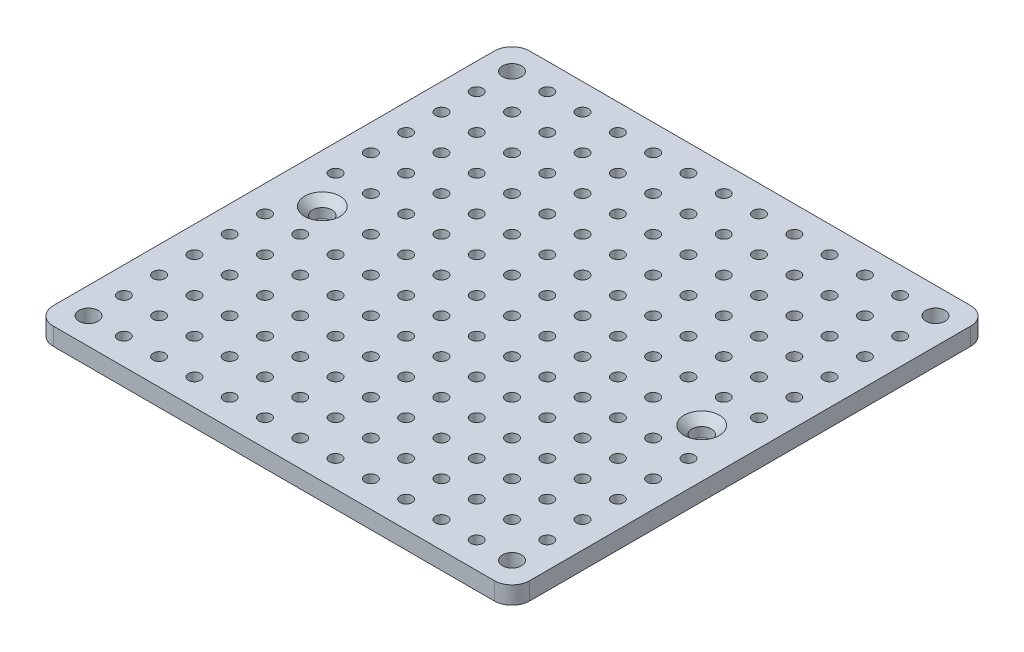
SolidWorks part; units mm, degrees
material "1060 Alloy"
ref_plane "Front Plane" through (0, 0, 0) normal (0, 0, 1) x (1, 0, 0)
ref_plane "Top Plane" through (0, 0, 0) normal (0, 1, 0) x (1, 0, 0)
ref_plane "Right Plane" through (0, 0, 0) normal (1, 0, 0) x (0, 0, -1)
sketch "Sketch1" plane through (0, 0, 0) normal (0, 1, 0) x (1, 0, 0)
  line L1 (-135, 135) -> (135, 135)
  line L2 (-135, 135) -> (-135, -135)
  line L3 (-135, -135) -> (135, -135)
  line L4 (135, 135) -> (135, -135)
  line L5 (-135, 135) -> (135, -135) construction
  line L6 (-135, -135) -> (135, 135) construction
  point P0 (0, 0)
  dimension "D1" = 270
  dimension "D2" = 270
extrude "Boss-Extrude1" add sketch "Sketch1" along normal blind 10
sketch "Sketch3" plane through (0, 10, 0) normal (0, 1, 0) x (1, 0, 0)
  circle A110 centre (0, 0) radius 4
  circle A111 centre (20, 0) radius 4
  circle A112 centre (40, 0) radius 4
  circle A113 centre (60, 0) radius 4
  circle A114 centre (80, 0) radius 4
  circle A115 centre (100, 0) radius 4
  circle A116 centre (120, 0) radius 4
  circle A117 centre (20, 20) radius 4
  circle A118 centre (40, 20) radius 4
  circle A119 centre (60, 20) radius 4
  circle A120 centre (80, 20) radius 4
  circle A121 centre (100, 20) radius 4
  circle A122 centre (120, 20) radius 4
  circle A123 centre (20, 40) radius 4
  circle A124 centre (40, 40) radius 4
  circle A125 centre (60, 40) radius 4
  circle A126 centre (80, 40) radius 4
  circle A127 centre (100, 40) radius 4
  circle A128 centre (120, 40) radius 4
  circle A129 centre (20, 60) radius 4
  circle A130 centre (40, 60) radius 4
  circle A131 centre (60, 60) radius 4
  circle A132 centre (80, 60) radius 4
  circle A133 centre (100, 60) radius 4
  circle A134 centre (120, 60) radius 4
  circle A135 centre (20, 80) radius 4
  circle A136 centre (40, 80) radius 4
  circle A137 centre (60, 80) radius 4
  circle A138 centre (80, 80) radius 4
  circle A139 centre (100, 80) radius 4
  circle A140 centre (120, 80) radius 4
  circle A141 centre (20, 100) radius 4
  circle A142 centre (40, 100) radius 4
  circle A143 centre (60, 100) radius 4
  circle A144 centre (80, 100) radius 4
  circle A145 centre (100, 100) radius 4
  circle A146 centre (120, 100) radius 4
  circle A147 centre (20, 120) radius 4
  circle A148 centre (40, 120) radius 4
  circle A149 centre (60, 120) radius 4
  circle A150 centre (80, 120) radius 4
  circle A151 centre (100, 120) radius 4
  circle A152 centre (120, 120) radius 4
  circle A153 centre (0, 20) radius 4
  circle A154 centre (0, 40) radius 4
  circle A155 centre (0, 60) radius 4
  circle A156 centre (0, 80) radius 4
  circle A157 centre (0, 100) radius 4
  circle A158 centre (0, 120) radius 4
  dimension "D1" = 8
sketch "Sketch4" plane through (0, 10, 0) normal (0, 1, 0) x (1, 0, 0)
  line L0 (135, 135) -> (-135, 135) construction
  line L1 (-135, 135) -> (-75.8392, 135)
  line L2 (-135, 135) -> (-135, 85)
  line L3 (-95, 75) -> (-75.8392, 75)
  line L4 (-75.8392, 135) -> (-75.8392, 75)
  line L5 (135, 135) -> (75.8392, 135)
  line L6 (135, 135) -> (135, 85)
  line L7 (95, 75) -> (75.8392, 75)
  line L8 (75.8392, 135) -> (75.8392, 75)
  line L9 (-70.3392, 105) -> (69.6608, 105)
  line L10 (-70.3392, 105) -> (-70.3392, 135)
  line L11 (-70.3392, 135) -> (69.6608, 135)
  line L12 (69.6608, 105) -> (69.6608, 135)
  line L13 (-135, 135) -> (-135, -135) construction
  line L14 (-135, -105) -> (135, -105)
  line L15 (-135, -105) -> (-135, -135)
  line L16 (-135, -135) -> (135, -135)
  line L17 (135, -105) -> (135, -135)
  line L18 (135, -135) -> (135, 135) construction
  line L19 (74.1608, -80) -> (95, -80)
  line L20 (74.1608, -80) -> (74.1608, -100)
  line L21 (74.1608, -100) -> (135, -100)
  line L22 (135, -90) -> (135, -100)
  line L24 (-95, -80) -> (-75.8392, -80)
  line L25 (-135, -90) -> (-135, -100)
  line L26 (-135, -100) -> (-75.8392, -100)
  line L27 (-75.8392, -80) -> (-75.8392, -100)
  line L29 (135, 85) -> (135, -90)
  line L31 (95, 75) -> (95, -80)
  line L33 (-135, 85) -> (-135, -90)
  line L35 (-95, 75) -> (-95, -80)
  dimension "D1" = 60
  dimension "D2" = 60
  dimension "D3" = 140
  dimension "D4" = 5.5
  dimension "D5" = 60
  dimension "D6" = 60
  dimension "D7" = 30
  dimension "D8" = 30
  dimension "D9" = 20
  dimension "D10" = 20
  dimension "D11" = 5
  dimension "D12" = 5
  dimension "D13" = 150
  dimension "D14" = 60
  dimension "D15" = 40
  dimension "D16" = 40
extrude "Boss-Extrude2" add sketch "Sketch4" against normal blind 10
fillet "Fillet1" radius 10 4 edges at (-135, 5, 135) (135, 5, 135) (135, 5, -135) (-135, 5, -135)
sketch "Sketch5" plane through (0, 10, 0) normal (0, 1, 0) x (1, 0, 0)
  circle A2 centre (107.5, 0) radius 5
  circle A3 centre (-107.5, 0) radius 5
  dimension "D1" = 10
  dimension "D2" = 10
  dimension "D3" = 107.5
  dimension "D4" = 107.5
sketch "Sketch6" plane through (0, 10, 0) normal (0, 1, 0) x (1, 0, 0)
  line L0 (31.6228, 15) -> (45, 15)
  line L1 (-45, 15) -> (-31.6228, 15)
  line L2 (-45, 15) -> (-45, -15)
  line L3 (-45, -15) -> (-31.6228, -15)
  line L4 (45, 15) -> (45, -15)
  line L5 (-45, 15) -> (45, -15) construction
  line L6 (-45, -15) -> (45, 15) construction
  line L7 (31.6228, -15) -> (45, -15)
  arc A0 (31.6228, 15) -> (-31.6228, 15) centre (0, 0) ccw
  arc A1 (-31.6228, -15) -> (31.6228, -15) centre (0, 0) ccw
  dimension "D1" = 70
  dimension "D2" = 90
  dimension "D3" = 30
extrude "Boss-Extrude3" add sketch "Sketch6" against normal blind 10
hole_wizard "M8x1.25 Tapped Hole1" positions "Sketch9" profile "Sketch10" tap size "M8x1.25" standard "ANSI Metric" end condition up to next
sketch "Sketch9" plane through (0, 10, 0) normal (0, 1, 0) x (1, 0, 0)
  point P0 (0, 120)
  point P3 (20, 120)
  point P6 (40, 120)
  point P9 (60, 120)
  point P12 (80, 120)
  point P15 (100, 120)
  point P18 (120, 120)
  point P21 (120, 100)
  point P24 (100, 100)
  point P27 (80, 100)
  point P30 (60, 100)
  point P33 (40, 100)
  point P36 (20, 100)
  point P39 (0, 100)
  point P42 (0, 80)
  point P45 (20, 80)
  point P48 (40, 80)
  point P51 (60, 80)
  point P54 (80, 80)
  point P57 (100, 80)
  point P60 (120, 80)
  point P63 (120, 60)
  point P66 (120, 40)
  point P69 (120, 20)
  point P72 (100, 20)
  point P75 (100, 40)
  point P78 (100, 60)
  point P81 (80, 60)
  point P84 (80, 40)
  point P87 (80, 20)
  point P90 (80, 0)
  point P93 (60, 0)
  point P96 (60, 20)
  point P99 (60, 40)
  point P102 (60, 60)
  point P105 (40, 60)
  point P108 (40, 40)
  point P111 (40, 20)
  point P114 (40, 0)
  point P117 (20, 0)
  point P120 (20, 20)
  point P123 (20, 40)
  point P126 (20, 60)
  point P129 (0, 60)
  point P132 (0, 40)
  point P135 (0, 20)
  point P138 (0, 0)
sketch "Sketch10" plane through (0, 10, -120) normal (1, 0, 0) x (0, 0, 1)
  line L0 (0, 0) -> (0, 10)
  line L1 (0, 10) -> (3.4, 10)
  line L2 (3.4, 10) -> (3.4, 0)
  line L5 (3.4, 0) -> (0, 0)
  line L11 (0, -6.35) -> (0, 107.95) construction
  dimension "Thru Tap Drill Dia." = 6.8
  dimension "Thru Tap Drill Depth" = 10
cosmetic thread "Hole Thread1" parameters "D2"=8
cosmetic thread "Hole Thread2" parameters "D2"=8
cosmetic thread "Hole Thread3" parameters "D2"=8
cosmetic thread "Hole Thread4" parameters "D2"=8
cosmetic thread "Hole Thread5" parameters "D2"=8
cosmetic thread "Hole Thread6" parameters "D2"=8
cosmetic thread "Hole Thread7" parameters "D2"=8
cosmetic thread "Hole Thread8" parameters "D2"=8
cosmetic thread "Hole Thread9" parameters "D2"=8
cosmetic thread "Hole Thread10" parameters "D2"=8
cosmetic thread "Hole Thread11" parameters "D2"=8
cosmetic thread "Hole Thread12" parameters "D2"=8
cosmetic thread "Hole Thread13" parameters "D2"=8
cosmetic thread "Hole Thread14" parameters "D2"=8
cosmetic thread "Hole Thread15" parameters "D2"=8
cosmetic thread "Hole Thread16" parameters "D2"=8
cosmetic thread "Hole Thread17" parameters "D2"=8
cosmetic thread "Hole Thread18" parameters "D2"=8
cosmetic thread "Hole Thread19" parameters "D2"=8
cosmetic thread "Hole Thread20" parameters "D2"=8
cosmetic thread "Hole Thread21" parameters "D2"=8
cosmetic thread "Hole Thread22" parameters "D2"=8
cosmetic thread "Hole Thread23" parameters "D2"=8
cosmetic thread "Hole Thread24" parameters "D2"=8
cosmetic thread "Hole Thread25" parameters "D2"=8
cosmetic thread "Hole Thread26" parameters "D2"=8
cosmetic thread "Hole Thread27" parameters "D2"=8
cosmetic thread "Hole Thread28" parameters "D2"=8
cosmetic thread "Hole Thread29" parameters "D2"=8
cosmetic thread "Hole Thread30" parameters "D2"=8
cosmetic thread "Hole Thread31" parameters "D2"=8
cosmetic thread "Hole Thread32" parameters "D2"=8
cosmetic thread "Hole Thread33" parameters "D2"=8
cosmetic thread "Hole Thread34" parameters "D2"=8
cosmetic thread "Hole Thread35" parameters "D2"=8
cosmetic thread "Hole Thread36" parameters "D2"=8
cosmetic thread "Hole Thread37" parameters "D2"=8
cosmetic thread "Hole Thread38" parameters "D2"=8
cosmetic thread "Hole Thread39" parameters "D2"=8
cosmetic thread "Hole Thread40" parameters "D2"=8
cosmetic thread "Hole Thread41" [suppressed] parameters "D2"=8
cosmetic thread "Hole Thread42" parameters "D2"=8
cosmetic thread "Hole Thread43" parameters "D2"=8
cosmetic thread "Hole Thread44" parameters "D2"=8
cosmetic thread "Hole Thread45" parameters "D2"=8
cosmetic thread "Hole Thread46" parameters "D2"=8
cosmetic thread "Hole Thread47" parameters "D2"=8
mirror "Mirror1" about plane through (0, 0, 0) normal (1, 0, 0) of "M8x1.25 Tapped Hole1"
mirror "Mirror2" about plane through (0, 0, 0) normal (0, 0, 1) of "Mirror1", "M8x1.25 Tapped Hole1"
hole_wizard "CSK for M10 Flat Head Machine Screw1" positions "Sketch11" profile "Sketch12" countersink size "M10" standard "ANSI Metric" end condition up to next
sketch "Sketch11" plane through (0, 10, 0) normal (0, 1, 0) x (1, 0, 0)
  point P0 (-107.5, 0)
  point P3 (107.5, 0)
sketch "Sketch12" plane through (-107.5, 10, 0) normal (1, 0, 0) x (0, 0, 1)
  line L0 (0, 0) -> (0, 10)
  line L1 (0, 10) -> (5.5, 10)
  line L2 (5.5, 10) -> (5.5, 4.5)
  line L3 (5.5, 4.5) -> (10, 0)
  line L5 (10, 0) -> (0, 0)
  line L6 (-5.5, 4.5) -> (-10, 0) construction
  line L11 (0, -6.35) -> (0, 107.95) construction
  dimension "Thru Hole Dia." = 11
  dimension "Thru Hole Depth" = 10
  dimension "Near C'Sink Dia." = 20
  dimension "Near C'Sink Angle" = 90
sketch "Sketch13" plane through (0, 10, 0) normal (0, 1, 0) x (1, 0, 0)
  circle A0 centre (-120, 120) radius 5
  circle A1 centre (120, 120) radius 5
  circle A2 centre (120, -120) radius 5
  circle A3 centre (-120, -120) radius 5
  dimension "D1" = 10
extrude "Cut-Extrude1" cut sketch "Sketch13" against normal through all
hole_wizard "M12x1.25 Tapped Hole3" positions "Sketch15" profile "Sketch16" tap size "M12x1.25" standard "ANSI Metric" end condition through all
sketch "Sketch15" plane through (0, 10, 0) normal (0, 1, 0) x (1, 0, 0)
  point P0 (-120, -120)
  point P3 (120, -120)
  point P6 (120, 120)
  point P9 (-120, 120)
sketch "Sketch16" plane through (-120, 10, 120) normal (1, 0, 0) x (0, 0, 1)
  line L0 (0, 0) -> (0, 10)
  line L1 (0, 10) -> (5.4, 10)
  line L2 (5.4, 10) -> (5.4, 0)
  line L5 (5.4, 0) -> (0, 0)
  line L11 (0, -6.35) -> (0, 107.95) construction
  dimension "Thru Tap Drill Dia." = 10.8
  dimension "Thru Tap Drill Depth" = 10
cosmetic thread "Hole Thread48" parameters "D2"=12
cosmetic thread "Hole Thread49" parameters "D2"=12
cosmetic thread "Hole Thread50" parameters "D2"=12
cosmetic thread "Hole Thread51" parameters "D2"=12
